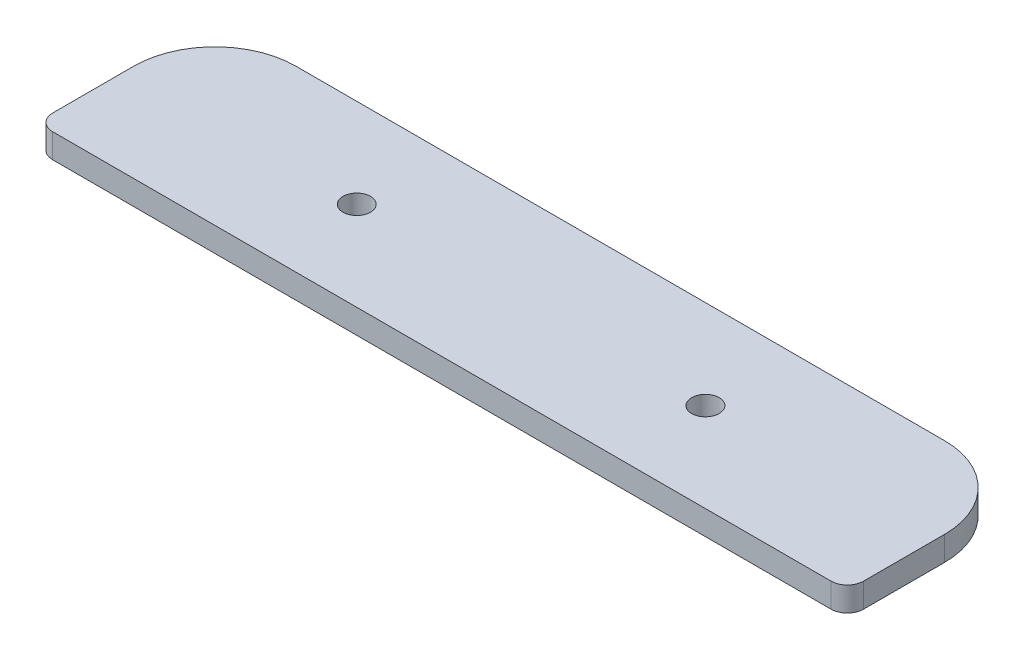
SolidWorks part; units mm, degrees
ref_plane "Front Plane" through (0, 0, 0) normal (0, 0, 1) x (1, 0, 0)
ref_plane "Top Plane" through (0, 0, 0) normal (0, 1, 0) x (1, 0, 0)
ref_plane "Right Plane" through (0, 0, 0) normal (1, 0, 0) x (0, 0, -1)
sketch "Sketch1" plane through (0, 12, 0) normal (0, 1, 0) x (1, 0, 0)
  line L0 (50, -49) -> (50, 18.1911) construction
  line L1 (-50, 50) -> (50, 50)
  line L3 (-50, 28) -> (50, 28)
  line L5 (-50, 50) -> (-50, 28)
  line L6 (50, 50) -> (50, 28)
  dimension "D1" = 22
extrude "Boss-Extrude1" add sketch "Sketch1" along normal blind 3
sketch "Sketch2" plane through (0, 15, 0) normal (0, 1, 0) x (1, 0, 0)
  line L0 (50, 50) -> (-50, 50) construction
  line L1 (50, 28) -> (50, 50) construction
  circle A0 centre (-21.5, 39) radius 1.7
  circle A1 centre (21.5, 39) radius 1.7
  dimension "D1" = 3.4
  dimension "D2" = 3.4
  dimension "D3" = 11
  dimension "D4" = 11
  dimension "D5" = 43
  dimension "D6" = 28.5
extrude "Cut-Extrude1" cut sketch "Sketch2" against normal up to surface (3 mm away) up to face at (0, 12, -39)
fillet "Fillet1" radius 10 2 edges at (-50, 13.5, -50) (50, 13.5, -50)
fillet "Fillet2" radius 2 2 edges at (-50, 13.5, -28) (50, 13.5, -28)
